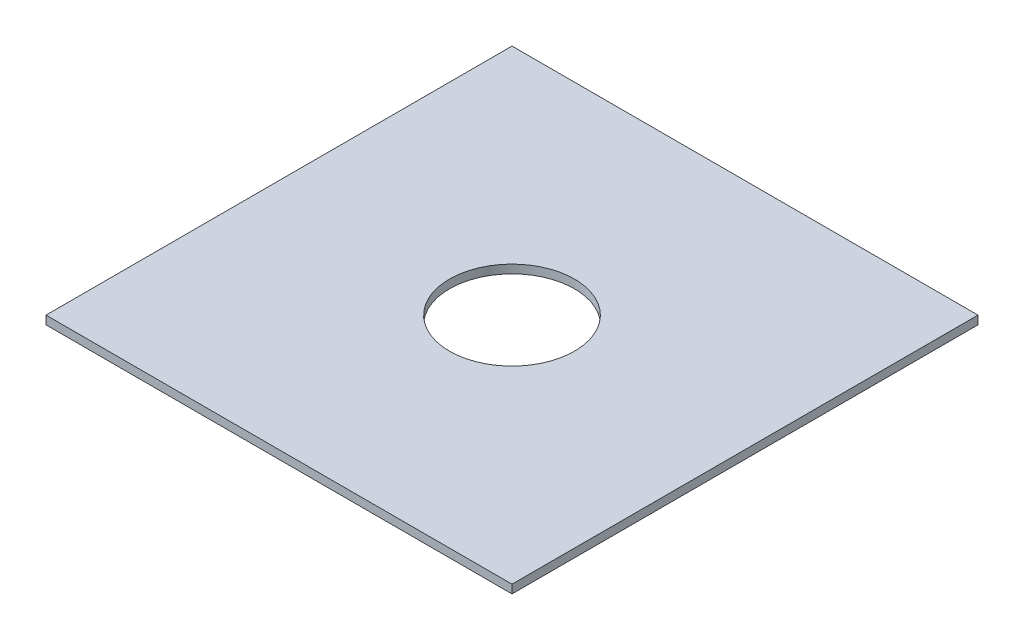
SolidWorks part; units mm, degrees
ref_plane "Front Plane" through (0, 0, 0) normal (0, 0, 1) x (1, 0, 0)
ref_plane "Top Plane" through (0, 0, 0) normal (0, 1, 0) x (1, 0, 0)
ref_plane "Right Plane" through (0, 0, 0) normal (1, 0, 0) x (0, 0, -1)
sketch "Sketch1" plane through (0, 0, 0) normal (0, 1, 0) x (1, 0, 0)
  line L1 (-55, 55) -> (55, 55)
  line L2 (-55, 55) -> (-55, -55)
  line L3 (-55, -55) -> (55, -55)
  line L4 (55, 55) -> (55, -55)
  line L5 (-55, 55) -> (55, -55) construction
  line L6 (-55, -55) -> (55, 55) construction
  point P0 (0, 0)
  dimension "D1" = 110
  dimension "D2" = 110
extrude "Boss-Extrude1" add sketch "Sketch1" along normal blind 2
sketch "Sketch2" plane through (0, 2, 0) normal (0, 1, 0) x (1, 0, 0)
  circle A0 centre (0, 0) radius 14.7553
extrude "Cut-Extrude1" cut sketch "Sketch2" against normal through all
